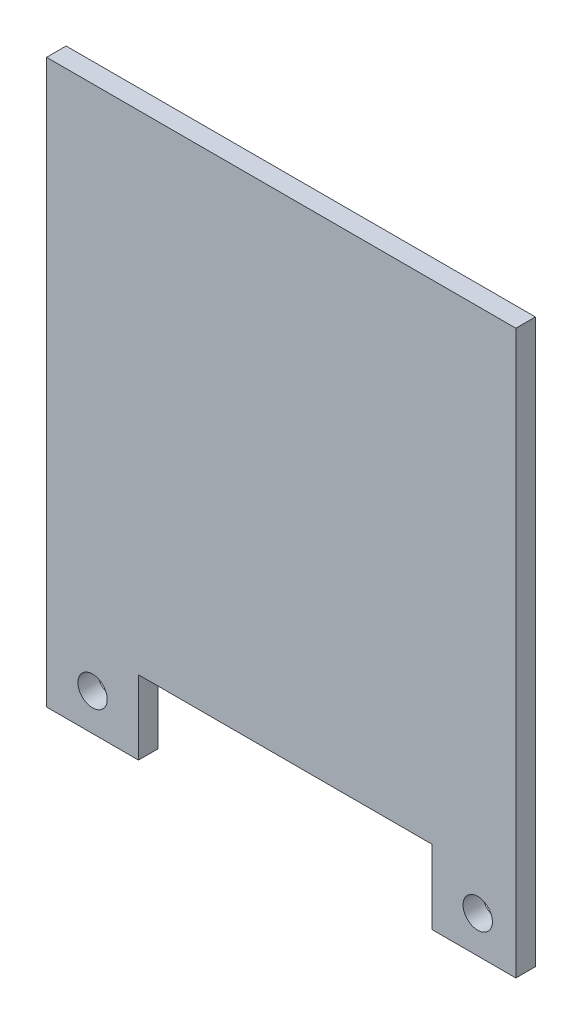
SolidWorks part; units mm, degrees
ref_plane "Front Plane" through (0, 0, 0) normal (0, 0, 1) x (1, 0, 0)
ref_plane "Top Plane" through (0, 0, 0) normal (0, 1, 0) x (1, 0, 0)
ref_plane "Right Plane" through (0, 0, 0) normal (1, 0, 0) x (0, 0, -1)
sketch "Sketch1" plane through (0, 0, 0) normal (0, 0, 1) x (1, 0, 0)
  line L0 (19.558, -36.5506) -> (30.48, -36.5506)
  line L1 (-30.48, 36.5506) -> (30.48, 36.5506)
  line L2 (-30.48, 36.5506) -> (-30.48, -36.5506)
  line L3 (-30.48, -36.5506) -> (-18.542, -36.5506)
  line L4 (30.48, 36.5506) -> (30.48, -36.5506)
  line L5 (-30.48, 36.5506) -> (30.48, -36.5506) construction
  line L6 (-30.48, -36.5506) -> (30.48, 36.5506) construction
  line L7 (-18.542, -26.9494) -> (19.558, -26.9494)
  line L8 (-18.542, -26.9494) -> (-18.542, -36.5506)
  line L10 (19.558, -26.9494) -> (19.558, -36.5506)
  point P0 (0, 0)
  dimension "D1" = 11.938
extrude "Boss-Extrude1" add sketch "Sketch1" along normal blind 2.54
sketch "Sketch2" plane through (0, 0, 2.54) normal (0, 0, 1) x (1, 0, 0)
  line L0 (-30.48, 36.5506) -> (-30.48, -36.5506) construction
  line L1 (-30.48, -36.5506) -> (-18.542, -36.5506) construction
  line L2 (19.558, -26.9494) -> (19.558, -36.5506) construction
  line L3 (19.558, -36.5506) -> (30.48, -36.5506) construction
  circle A0 centre (-24.511, -31.75) radius 1.905
  circle A1 centre (25.527, -31.75) radius 1.905
  dimension "D1" = 5.969
  dimension "D2" = 4.8006
  dimension "D3" = 5.969
  dimension "D4" = 4.8006
extrude "Cut-Extrude1" cut sketch "Sketch2" against normal blind 2.54
